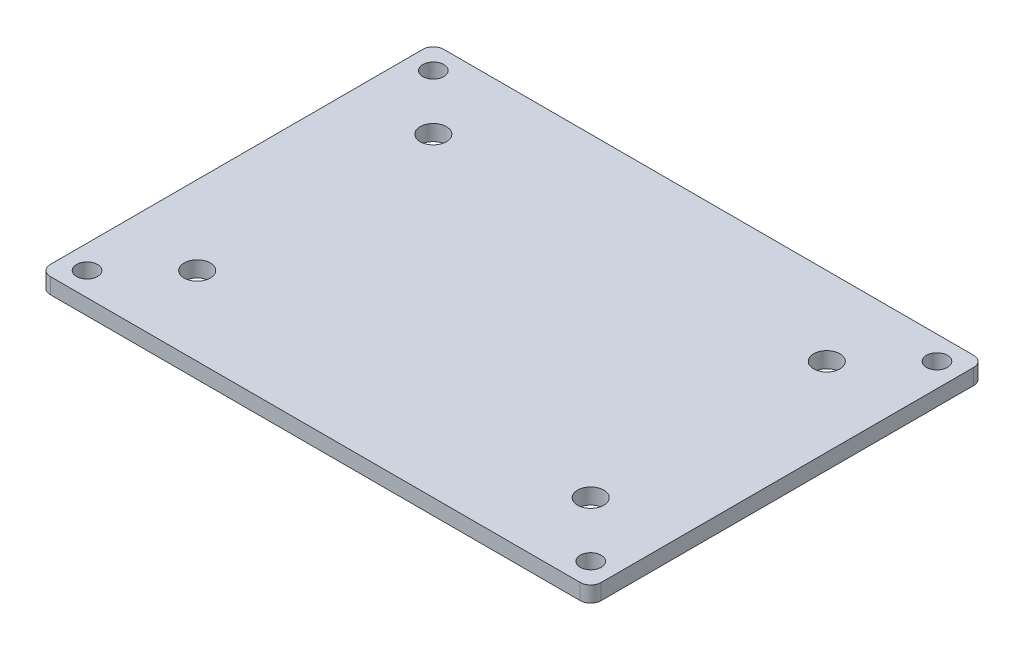
SolidWorks part; units mm, degrees
ref_plane "정면도" through (0, 0, 0) normal (0, 0, 1) x (1, 0, 0)
ref_plane "평면도" through (0, 0, 0) normal (0, 1, 0) x (1, 0, 0)
ref_plane "우측면도" through (0, 0, 0) normal (1, 0, 0) x (0, 0, -1)
sketch "스케치1" plane through (0, 0, 0) normal (0, 1, 0) x (1, 0, 0)
  line L1 (-52.5, -37.5) -> (52.5, -37.5)
  line L2 (-52.5, -37.5) -> (-52.5, 37.5)
  line L3 (-52.5, 37.5) -> (52.5, 37.5)
  line L4 (52.5, -37.5) -> (52.5, 37.5)
  line L5 (0, 37.5) -> (0, -37.5) construction
  line L6 (-52.5, 0) -> (52.5, 0) construction
  circle A0 centre (-48, 33) radius 2
  circle A1 centre (-48, -33) radius 2
  circle A2 centre (48, -33) radius 2
  circle A3 centre (48, 33) radius 2
  point P0 (0, 0)
  dimension "D3" = 4
  dimension "D1" = 75
  dimension "D2" = 105
  dimension "D4" = 4.5
  dimension "D5" = 4.5
  dimension "D6" = 4.5
  dimension "D7" = 4.5
extrude "보스-돌출1" add sketch "스케치1" along normal blind 3
fillet "필렛1" radius 2 4 edges at (-52.5, 1.5, -37.5) (-52.5, 1.5, 37.5) (52.5, 1.5, -37.5) (52.5, 1.5, 37.5)
sketch "스케치2" plane through (0, 3, 0) normal (0, 1, 0) x (1, 0, 0)
  line L0 (-52.5, 35.5) -> (-52.5, -35.5) construction
  line L1 (-50.5, -37.5) -> (50.5, -37.5) construction
  line L2 (52.5, -35.5) -> (52.5, 35.5) construction
  line L3 (50.5, 37.5) -> (-50.5, 37.5) construction
  circle A0 centre (-37.5, -22.5) radius 2.5
  circle A1 centre (37.5, -22.5) radius 2.5
  circle A2 centre (37.5, 22.5) radius 2.5
  circle A3 centre (-37.5, 22.5) radius 2.5
  dimension "D1" = 5
  dimension "D2" = 15
  dimension "D3" = 15
  dimension "D4" = 15
  dimension "D6" = 15
  dimension "D7" = 15
  dimension "D9" = 15
  dimension "D5" = 15
  dimension "D8" = 15
extrude "컷-돌출1" cut sketch "스케치2" against normal blind 10
